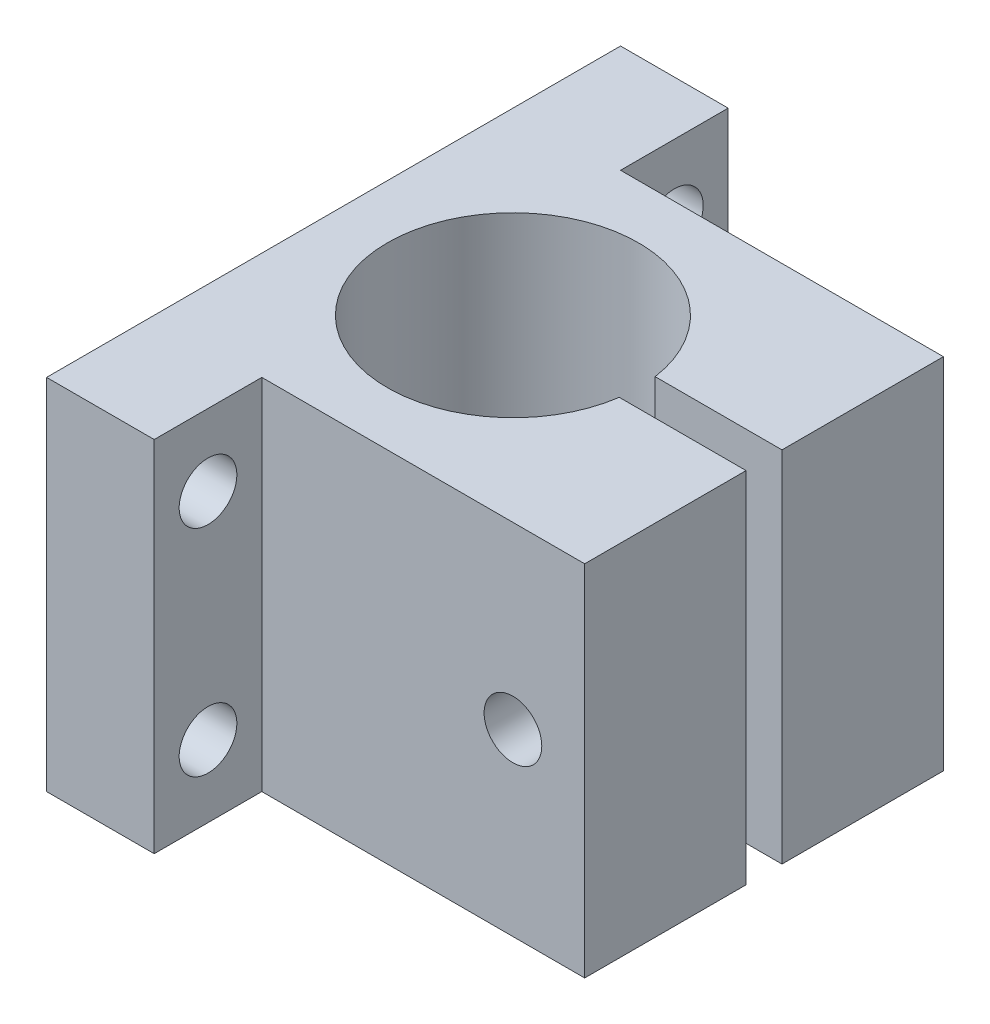
SolidWorks part; units mm, degrees
material "6061 Alloy"
ref_plane "Front Plane" through (0, 0, 0) normal (0, 0, 1) x (1, 0, 0)
ref_plane "Top Plane" through (0, 0, 0) normal (0, 1, 0) x (1, 0, 0)
ref_plane "Right Plane" through (0, 0, 0) normal (1, 0, 0) x (0, 0, -1)
sketch "Sketch1" plane through (0, 0, 0) normal (0, 1, 0) x (1, 0, 0)
  line L1 (-19.05, 25.4) -> (19.05, 25.4)
  line L2 (-19.05, 25.4) -> (-19.05, -25.4)
  line L3 (-19.05, -25.4) -> (19.05, -25.4)
  line L4 (19.05, 25.4) -> (19.05, -25.4)
  line L5 (-19.05, 25.4) -> (19.05, -25.4) construction
  line L6 (-19.05, -25.4) -> (19.05, 25.4) construction
  point P0 (0, 0)
  dimension "D1" = 38.1
  dimension "D2" = 50.8
extrude "Boss-Extrude1" add sketch "Sketch1" along normal blind 31.75
sketch "Sketch2" plane through (0, 31.75, 0) normal (0, 1, 0) x (1, 0, 0)
  line L0 (-19.05, 25.4) -> (-19.05, -25.4) construction
  circle A0 centre (-3.175, 0) radius 11.1125
  dimension "D1" = 22.225
  dimension "D2" = 15.875
extrude "Cut-Extrude1" cut sketch "Sketch2" against normal through all
sketch "Sketch3" plane through (0, 31.75, 0) normal (0, 1, 0) x (1, 0, 0)
  line L0 (-19.05, -25.4) -> (19.05, -25.4) construction
  line L1 (19.05, 25.4) -> (-9.525, 25.4)
  line L2 (19.05, 25.4) -> (19.05, 15.875)
  line L3 (19.05, 15.875) -> (-9.525, 15.875)
  line L4 (-9.525, 25.4) -> (-9.525, 15.875)
  line L5 (-9.525, -25.4) -> (19.05, -25.4)
  line L6 (-9.525, -25.4) -> (-9.525, -15.875)
  line L7 (-9.525, -15.875) -> (19.05, -15.875)
  line L8 (19.05, -25.4) -> (19.05, -15.875)
  line L9 (19.05, -25.4) -> (19.05, 25.4) construction
  line L10 (-19.05, 25.4) -> (-19.05, -25.4) construction
  dimension "D1" = 9.525
  dimension "D2" = 9.525
extrude "Cut-Extrude2" cut sketch "Sketch3" against normal through all
hole_wizard "#10 Clearance Hole1" positions "Sketch5" profile "Sketch4" hole size "#10" standard "ANSI Inch"
sketch "Sketch5" plane through (-9.525, 0, 0) normal (1, 0, 0) x (0, 0, -1)
  line L13 (-20.6375, 25.4) -> (20.6375, 25.4) construction
  line L14 (-20.6375, 25.4) -> (-20.6375, 6.35) construction
  line L15 (-20.6375, 6.35) -> (20.6375, 6.35) construction
  line L16 (20.6375, 25.4) -> (20.6375, 6.35) construction
  line L17 (0, 6.35) -> (0, 0) construction
  line L19 (-15.875, 31.75) -> (-25.4, 31.75) construction
  line L20 (-25.4, 0) -> (-25.4, 31.75) construction
  point P303 (-20.6375, 25.4)
  point P304 (20.6375, 6.35)
  point P557 (-20.6375, 6.35)
  point P558 (20.6375, 25.4)
  dimension "D1" = 6.35
  dimension "D2" = 4.7625
  dimension "D3" = 6.35
sketch "Sketch4" plane through (-9.525, 25.4, 20.6375) normal (0, 1, 0) x (0, 0, -1)
  line L0 (0, 0) -> (0, 11.1858)
  line L1 (0, 11.1858) -> (2.5527, 9.652)
  line L2 (2.5527, 9.652) -> (2.5527, 0)
  line L5 (2.5527, 0) -> (0, 0)
  line L10 (0, 11.1858) -> (-2.5527, 9.652) construction
  line L11 (0, -6.35) -> (0, 107.95) construction
  dimension "Hole Dia." = 5.1054
  dimension "Hole Depth" = 9.652
  dimension "Drill Angle" = 118
sketch "Sketch6" plane through (19.05, 0, 0) normal (1, 0, 0) x (0, 0, -1)
  line L0 (-15.875, 0) -> (15.875, 0) construction
  line L1 (-1.5875, 0) -> (1.5875, 0)
  line L2 (-1.5875, 0) -> (-1.5875, 31.75)
  line L3 (-1.5875, 31.75) -> (1.5875, 31.75)
  line L4 (1.5875, 0) -> (1.5875, 31.75)
  line L5 (-15.875, 31.75) -> (15.875, 31.75) construction
  dimension "D1" = 3.175
extrude "Cut-Extrude3" cut sketch "Sketch6" against normal blind 24.13
hole_wizard "#10 Clearance Hole2" positions "Sketch8" profile "Sketch9" hole size "#10" standard "ANSI Inch" end condition through all
sketch "Sketch8" plane through (0, 0, 15.875) normal (0, 0, 1) x (1, 0, 0)
  line L0 (12.7, 31.75) -> (12.7, 0) construction
  line L1 (19.05, 31.75) -> (-9.525, 31.75) construction
  line L2 (19.05, 0) -> (-9.525, 0) construction
  line L3 (19.05, 0) -> (19.05, 31.75) construction
  point P9 (12.7, 15.875)
  point P13 (12.7, 15.875)
  dimension "D1" = 15.875
  dimension "D2" = 15.875
  dimension "D3" = 6.35
sketch "Sketch9" plane through (12.7, 15.875, 15.875) normal (1, 0, 0) x (0, -1, 0)
  line L0 (0, 0) -> (0, 41.275)
  line L1 (0, 41.275) -> (2.5527, 41.275)
  line L2 (2.5527, 41.275) -> (2.5527, 0)
  line L5 (2.5527, 0) -> (0, 0)
  line L11 (0, -6.35) -> (0, 107.95) construction
  dimension "Thru Hole Dia." = 5.1054
  dimension "Thru Hole Depth" = 41.275
